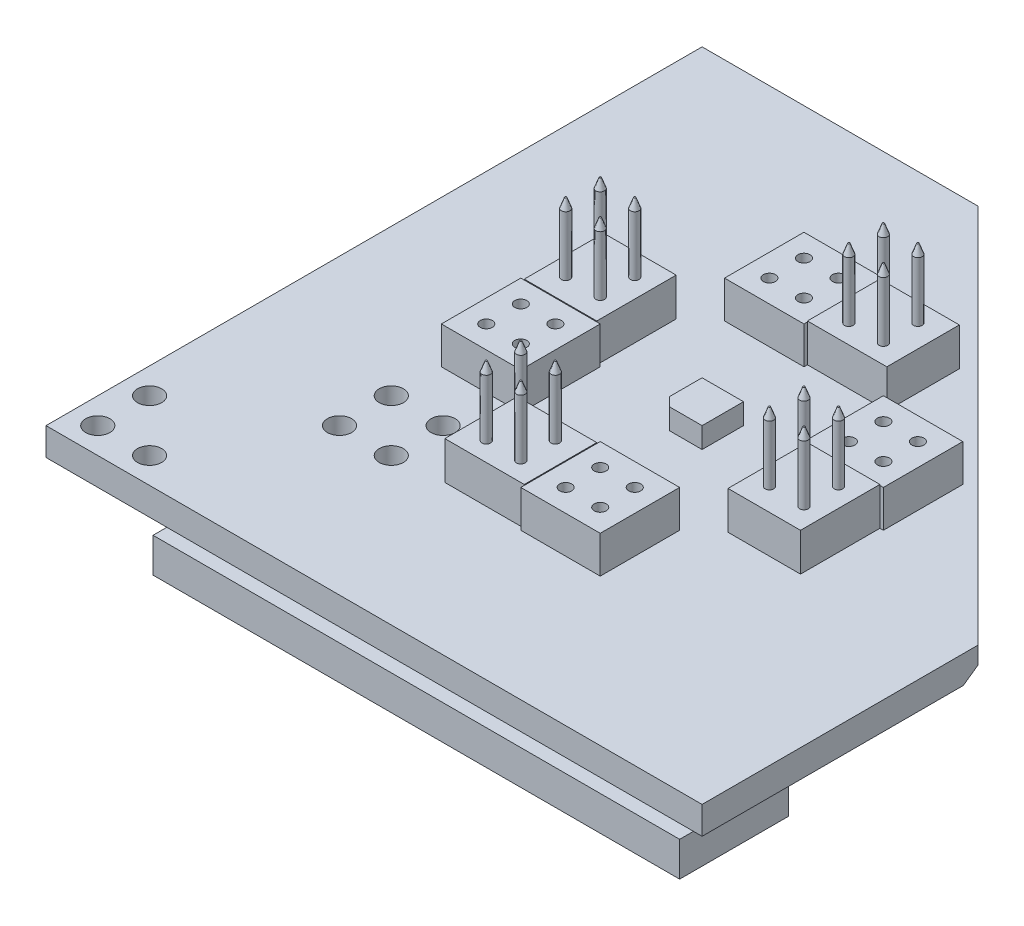
SolidWorks part; units mm, degrees
ref_plane "Front" through (0, 0, 0) normal (0, 0, 1) x (1, 0, 0)
ref_plane "Top" through (0, 0, 0) normal (0, 1, 0) x (1, 0, 0)
ref_plane "Right" through (0, 0, 0) normal (1, 0, 0) x (0, 0, -1)
sketch "Sketch1" plane through (0, 0, 0) normal (0, 1, 0) x (1, 0, 0)
  line L0 (19, -3.0194) -> (-3.0194, 19)
  line L1 (-19, 19) -> (-3.0194, 19)
  line L2 (-19, 19) -> (-19, -19)
  line L3 (-19, -19) -> (19, -19)
  line L4 (19, -3.0194) -> (19, -19)
  dimension "D1" = 19
  dimension "D2" = 19
  dimension "D3" = 19
  dimension "D4" = 19
  dimension "D5" = 45
  dimension "D6" = 11.3
extrude "Extrude1" add sketch "Sketch1" along normal blind 1.6
sketch "Sketch2" plane through (0, 1.6, 0) normal (0, 1, 0) x (-1, 0, 0)
  line L0 (-10.5, -4.6) -> (-10.5, 0)
  line L1 (4.6, -10.5) -> (0, -10.5)
  line L2 (4.6, -10.5) -> (4.6, -5.9)
  line L3 (4.6, -5.9) -> (0, -5.9)
  line L4 (0, -10.5) -> (0, -5.9)
  line L5 (-10.5, -4.6) -> (-5.9, -4.6)
  line L6 (-5.9, -4.6) -> (-5.9, 0)
  line L7 (-10.5, 0) -> (-5.9, 0)
  line L8 (-4.6, 10.5) -> (0, 10.5)
  line L9 (-4.6, 10.5) -> (-4.6, 5.9)
  line L10 (-4.6, 5.9) -> (0, 5.9)
  line L11 (0, 10.5) -> (0, 5.9)
  line L12 (10.5, 4.6) -> (10.5, 0)
  line L13 (10.5, 4.6) -> (5.9, 4.6)
  line L14 (5.9, 4.6) -> (5.9, 0)
  line L15 (10.5, 0) -> (5.9, 0)
  dimension "D1" = 4.6
  dimension "D2" = 4.6
  dimension "D3" = 5.9
  dimension "D4" = 5.9
extrude "Extrude2" add sketch "Sketch2" along normal blind 2.15
sketch "Sketch3" plane through (0, 1.6, 0) normal (0, 1, 0) x (-1, 0, 0)
  line L0 (0, -5.9) -> (0, -10.5) construction
  line L1 (-4.6, -10.3) -> (0, -10.3)
  line L2 (-4.6, -10.3) -> (-4.6, -6.1)
  line L3 (-4.6, -6.1) -> (0, -6.1)
  line L4 (0, -10.3) -> (0, -6.1)
  line L5 (-6.1, 4.6) -> (-6.1, 0)
  line L6 (-10.3, 0) -> (-6.1, 0)
  line L7 (-10.3, 4.6) -> (-6.1, 4.6)
  line L8 (-10.3, 4.6) -> (-10.3, 0)
  line L9 (4.6, 6.1) -> (0, 6.1)
  line L10 (0, 10.3) -> (0, 6.1)
  line L11 (4.6, 10.3) -> (4.6, 6.1)
  line L12 (4.6, 10.3) -> (0, 10.3)
  line L13 (6.1, -4.6) -> (6.1, 0)
  line L14 (10.3, 0) -> (6.1, 0)
  line L15 (10.3, -4.6) -> (6.1, -4.6)
  line L16 (10.3, -4.6) -> (10.3, 0)
  dimension "D1" = 4.6
  dimension "D2" = 4.2
  dimension "D3" = 6.1
  dimension "D4" = 6.1
extrude "Extrude3" add sketch "Sketch3" along normal blind 2.2
sketch "Sketch4" plane through (0, 3.75, 0) normal (0, 1, 0) x (-1, 0, 0)
  line L0 (2.3, -10.5) -> (2.3, -5.9) construction
  line L2 (4.6, -5.9) -> (0, -5.9) construction
  line L3 (4.6, -8.2) -> (0, -8.2) construction
  line L4 (0, -10.5) -> (4.6, -10.5) construction
  line L6 (4.6, -10.5) -> (4.6, -5.9) construction
  circle A0 centre (3.3, -9.2) radius 0.35
  circle A1 centre (1.3, -9.2) radius 0.35
  circle A2 centre (1.3, -7.2) radius 0.35
  circle A3 centre (3.3, -7.2) radius 0.35
  circle A4 centre (-9.2, -3.3) radius 0.35
  circle A5 centre (-9.2, -1.3) radius 0.35
  circle A6 centre (-7.2, -1.3) radius 0.35
  circle A7 centre (-7.2, -3.3) radius 0.35
  circle A8 centre (-3.3, 9.2) radius 0.35
  circle A9 centre (-1.3, 9.2) radius 0.35
  circle A10 centre (-1.3, 7.2) radius 0.35
  circle A11 centre (-3.3, 7.2) radius 0.35
  circle A12 centre (9.2, 3.3) radius 0.35
  circle A13 centre (9.2, 1.3) radius 0.35
  circle A14 centre (7.2, 1.3) radius 0.35
  circle A15 centre (7.2, 3.3) radius 0.35
  dimension "D3" = 0.7
  dimension "D1" = 1
  dimension "D2" = 1
extrude "Cut-Extrude1" cut sketch "Sketch4" against normal up to surface (2.15 mm away) up to face at (0, 1.6, 8.2)
sketch "Sketch5" plane through (0, 3.8, 0) normal (0, 1, 0) x (-1, 0, 0)
  line L0 (-2.3, -10.3) -> (-2.3, -6.1) construction
  line L1 (-4.6, -10.3) -> (0, -10.3) construction
  line L2 (0, -6.1) -> (-4.6, -6.1) construction
  line L3 (0, -8.2) -> (-4.6, -8.2) construction
  line L4 (0, -10.3) -> (0, -6.1) construction
  line L5 (-4.6, -6.1) -> (-4.6, -10.3) construction
  circle A0 centre (-1.3, -9.2) radius 0.25
  circle A1 centre (-3.3, -9.2) radius 0.25
  circle A2 centre (-3.3, -7.2) radius 0.25
  circle A3 centre (-1.3, -7.2) radius 0.25
  circle A4 centre (-7.2, 1.3) radius 0.25
  circle A5 centre (-9.2, 1.3) radius 0.25
  circle A6 centre (-9.2, 3.3) radius 0.25
  circle A7 centre (-7.2, 3.3) radius 0.25
  circle A8 centre (1.3, 7.2) radius 0.25
  circle A9 centre (1.3, 9.2) radius 0.25
  circle A10 centre (3.3, 9.2) radius 0.25
  circle A11 centre (3.3, 7.2) radius 0.25
  circle A12 centre (7.2, -1.3) radius 0.25
  circle A13 centre (9.2, -1.3) radius 0.25
  circle A14 centre (9.2, -3.3) radius 0.25
  circle A15 centre (7.2, -3.3) radius 0.25
  dimension "D3" = 0.5
  dimension "D1" = 1
  dimension "D2" = 1
extrude "Extrude4" add sketch "Sketch5" along normal blind 4
chamfer "Chamfer1" distance 0.2 angle 70 16 edges at (-1.3, 7.8, 9.45) (-3.3, 7.8, 8.95) (-3.3, 7.8, 7.45) (-1.3, 7.8, 6.95) (7.2, 7.8, 3.55) (9.2, 7.8, 3.05) (9.2, 7.8, 1.55) (7.2, 7.8, 1.05) (1.3, 7.8, -7.45) (3.3, 7.8, -6.95) (3.3, 7.8, -9.45) (1.3, 7.8, -8.95) (-9.2, 7.8, -1.05) (-7.2, 7.8, -3.05) (-9.2, 7.8, -3.55) (-7.2, 7.8, -1.55)
sketch "Sketch6" plane through (0, 0, 0) normal (0, -1, 0) x (1, 0, 0)
  line L0 (-19, -19) -> (-19, 19) construction
  line L1 (-13.5, -18.5) -> (-19.8, -18.5)
  line L2 (-19.8, -18.5) -> (-19.8, 12)
  line L3 (-19.8, 12) -> (-13.5, 12)
  line L4 (-13.5, 12) -> (-13.5, -18.5)
  line L8 (0, 0) -> (-19, 19) construction
  line L9 (18.5, 13.5) -> (18.5, 19.8)
  line L10 (18.5, 19.8) -> (-12, 19.8)
  line L11 (-12, 19.8) -> (-12, 13.5)
  line L12 (-12, 13.5) -> (18.5, 13.5)
  dimension "D1" = 30.5
  dimension "D2" = 6.3
  dimension "D3" = 13.5
  dimension "D4" = 18.5
extrude "Extrude5" add sketch "Sketch6" along normal blind 2
sketch "Sketch7" plane through (0, 0, 0) normal (0, -1, 0) x (1, 0, 0)
  line L0 (-19, 19) -> (-12, 19) construction
  line L1 (-8.75, 3.25) -> (-1.75, 3.25)
  line L2 (-8.75, 3.25) -> (-8.75, -3.75)
  line L3 (-8.75, -3.75) -> (-1.75, -3.75)
  line L4 (-1.75, 3.25) -> (-1.75, -3.75)
  line L5 (-19, 12) -> (-19, 19) construction
  dimension "D1" = 7
  dimension "D2" = 7
  dimension "D3" = 15.75
  dimension "D4" = 10.25
extrude "Extrude6" add sketch "Sketch7" along normal blind 1
chamfer "Chamfer2" distance 0.6 angle 45 1 edges at (7.9903, 0, -7.9903)
sketch "Sketch8" plane through (0, 1.6, 0) normal (0, 1, 0) x (-1, 0, 0)
  line L0 (1.2, 0.7) -> (0.7, 1.2)
  line L1 (1.2, -1.2) -> (-1.2, -1.2)
  line L2 (1.2, -1.2) -> (1.2, 0.7)
  line L3 (0.7, 1.2) -> (-1.2, 1.2)
  line L4 (-1.2, -1.2) -> (-1.2, 1.2)
  dimension "D1" = 1.2
  dimension "D2" = 1.2
  dimension "D3" = 1.2
  dimension "D4" = 1.2
  dimension "D5" = 0.5
  dimension "D6" = 0.5
extrude "Extrude7" add sketch "Sketch8" along normal blind 1.2
sketch "Sketch9" plane through (0, 0, 0) normal (0, -1, 0) x (1, 0, 0)
  line L0 (19, 19) -> (19, 3.8679) construction
  line L1 (9.5, 1.7) -> (7.5, 1.7)
  line L2 (9.5, 1.7) -> (9.5, -0.3)
  line L3 (9.5, -0.3) -> (7.5, -0.3)
  line L4 (7.5, 1.7) -> (7.5, -0.3)
  line L5 (18.5, 19) -> (19, 19) construction
  line L6 (-19, 19) -> (-12, 19) construction
  line L7 (-0.35, 6.15) -> (-2.35, 6.15)
  line L8 (-0.35, 6.15) -> (-0.35, 4.15)
  line L9 (-0.35, 4.15) -> (-2.35, 4.15)
  line L10 (-2.35, 6.15) -> (-2.35, 4.15)
  dimension "D1" = 9.5
  dimension "D2" = 17.3
  dimension "D3" = 2
  dimension "D4" = 2
  dimension "D5" = 19.35
  dimension "D6" = 12.85
  dimension "D7" = 2
  dimension "D8" = 2
extrude "Extrude8" add sketch "Sketch9" along normal blind 0.9
sketch "Sketch10" plane through (0, 0, 0) normal (0, -1, 0) x (1, 0, 0)
  line L0 (19, 19) -> (19, 3.8679) construction
  line L1 (1.35, 2.8) -> (0.6, 2.8)
  line L2 (1.55, 2.6) -> (1.55, -0.2)
  line L3 (1.35, -0.4) -> (0.6, -0.4)
  line L4 (0.4, 2.6) -> (0.4, -0.2)
  line L5 (-19, 19) -> (-12, 19) construction
  arc A0 (0.4, -0.2) -> (0.6, -0.4) centre (0.6, -0.2) ccw
  arc A1 (0.6, 2.8) -> (0.4, 2.6) centre (0.6, 2.6) ccw
  arc A2 (1.55, 2.6) -> (1.35, 2.8) centre (1.35, 2.6) ccw
  arc A3 (1.35, -0.4) -> (1.55, -0.2) centre (1.35, -0.2) ccw
  point P10 (0.4, -0.4)
  point P15 (1.55, 2.8)
  point P18 (1.55, -0.4)
  dimension "D5" = 0.2
  dimension "D1" = 17.45
  dimension "D2" = 16.2
  dimension "D3" = 1.15
  dimension "D4" = 3.2
extrude "Extrude9" add sketch "Sketch10" along normal blind 1
sketch "Sketch11" plane through (0, 0, 0) normal (0, -1, 0) x (1, 0, 0)
  line L0 (19, 19) -> (19, 3.8679) construction
  line L1 (9.35, 6.9) -> (7.75, 6.9)
  line L2 (9.35, 6.9) -> (9.35, 6.1)
  line L3 (9.35, 6.1) -> (7.75, 6.1)
  line L4 (7.75, 6.9) -> (7.75, 6.1)
  line L5 (-19, 19) -> (-12, 19) construction
  line L6 (-19, 12) -> (-19, 19) construction
  line L7 (-10.15, -6.9) -> (-10.95, -6.9)
  line L8 (-10.15, -6.9) -> (-10.15, -5.3)
  line L9 (-10.15, -5.3) -> (-10.95, -5.3)
  line L10 (-10.95, -6.9) -> (-10.95, -5.3)
  line L11 (-3.8679, -19) -> (-19, -19) construction
  line L12 (-19, -19) -> (-19, -18.5) construction
  line L13 (-2.9, -14.85) -> (-3.7, -14.85)
  line L14 (-2.9, -14.85) -> (-2.9, -13.25)
  line L15 (-2.9, -13.25) -> (-3.7, -13.25)
  line L16 (-3.7, -14.85) -> (-3.7, -13.25)
  line L18 (-0.3, -12.1) -> (-1.1, -12.1)
  line L19 (-0.3, -12.1) -> (-0.3, -10.5)
  line L20 (-0.3, -10.5) -> (-1.1, -10.5)
  line L21 (-1.1, -12.1) -> (-1.1, -10.5)
  point P20 (-19, -18.75)
  point P27 (-19, -18.75)
  dimension "D1" = 9.65
  dimension "D2" = 12.1
  dimension "D3" = 1.6
  dimension "D4" = 0.8
  dimension "D5" = 8.05
  dimension "D6" = 12.1
  dimension "D7" = 1.6
  dimension "D8" = 0.8
  dimension "D9" = 15.3
  dimension "D10" = 4.15
  dimension "D11" = 1.6
  dimension "D12" = 0.8
  dimension "D13" = 17.9
  dimension "D14" = 6.9
  dimension "D15" = 1.6
  dimension "D16" = 0.8
extrude "Extrude10" add sketch "Sketch11" along normal blind 0.5
sketch "Sketch12" plane through (0, 0, 0) normal (0, -1, 0) x (1, 0, 0)
  line L0 (-19, 12) -> (-19, 19) construction
  line L1 (-11.3, -16.3) -> (-9.6, -16.3)
  line L2 (-11.3, -16.3) -> (-11.3, -12.6)
  line L3 (-11.3, -12.6) -> (-10.6, -12.6)
  line L4 (-4.6, -16.3) -> (-4.6, -12.6)
  line L5 (-3.8679, -19) -> (-19, -19) construction
  line L6 (-6.4, -16.3) -> (-4.6, -16.3)
  line L7 (-9.7, -12.6) -> (-8.45, -12.6)
  line L8 (-6.4, -16.3) -> (-6.4, -18.2)
  line L9 (-6.4, -18.2) -> (-9.6, -18.2)
  line L10 (-9.6, -16.3) -> (-9.6, -18.2)
  line L11 (-5.3, -12.6) -> (-4.6, -12.6)
  line L12 (-5.3, -12.6) -> (-5.3, -10.7)
  line L13 (-5.3, -10.7) -> (-6.2, -10.7)
  line L14 (-6.2, -12.6) -> (-6.2, -10.7)
  line L16 (-7.55, -12.6) -> (-7.55, -10.7)
  line L17 (-7.55, -10.7) -> (-8.45, -10.7)
  line L18 (-8.45, -12.6) -> (-8.45, -10.7)
  line L19 (-7.55, -12.6) -> (-6.2, -12.6)
  line L20 (-9.7, -12.6) -> (-9.7, -10.7)
  line L21 (-9.7, -10.7) -> (-10.6, -10.7)
  line L22 (-10.6, -12.6) -> (-10.6, -10.7)
  dimension "D1" = 7.7
  dimension "D2" = 2.7
  dimension "D3" = 6.7
  dimension "D4" = 3.7
  dimension "D5" = 1.9
  dimension "D6" = 3.2
  dimension "D7" = 1.7
  dimension "D8" = 0.9
  dimension "D9" = 1.9
  dimension "D10" = 0.9
  dimension "D11" = 1.9
  dimension "D12" = 0.9
  dimension "D13" = 1.9
  dimension "D14" = 2.85
  dimension "D15" = 0.7
  dimension "D16" = 0.7
extrude "Extrude11" add sketch "Sketch12" along normal blind 0.3
sketch "Sketch13" plane through (0, -0.3, 0) normal (0, -1, 0) x (1, 0, 0)
  line L1 (-4.61, -16.29) -> (-11.29, -16.29)
  line L2 (-4.61, -16.29) -> (-4.61, -12.61)
  line L3 (-4.61, -12.61) -> (-11.29, -12.61)
  line L4 (-11.29, -16.29) -> (-11.29, -12.61)
  line L5 (-6.4, -16.3) -> (-4.6, -16.3) construction
  line L6 (-4.6, -16.3) -> (-4.6, -12.6) construction
  line L7 (-11.3, -12.6) -> (-11.3, -16.3) construction
  line L8 (-10.6, -12.6) -> (-11.3, -12.6) construction
  dimension "D1" = 0.01
  dimension "D2" = 0.01
  dimension "D3" = 0.01
  dimension "D4" = 0.01
extrude "Extrude12" add sketch "Sketch13" along normal blind 1.5
sketch "Sketch14" plane through (0, 0, 0) normal (0, -1, 0) x (1, 0, 0)
  line L0 (-19, 12) -> (-19, 19) construction
  line L1 (-19, 19) -> (-12, 19) construction
  line L2 (0, 0) -> (-19, 19) construction
  circle A0 centre (-17.5, 17.5) radius 0.7
  circle A1 centre (-17.5, 14.5) radius 0.7
  circle A2 centre (-10.5, 10.5) radius 0.7
  circle A3 centre (-7.5, 7.5) radius 0.7
  circle A4 centre (-10.5, 7.5) radius 0.7
  circle A5 centre (-14.5, 17.5) radius 0.7
  circle A6 centre (-7.5, 10.5) radius 0.7
  dimension "D1" = 1.4
  dimension "D5" = 1.4
  dimension "D7" = 1.4
  dimension "D8" = 1.4
  dimension "D11" = 1.4
  dimension "D2" = 1.5
  dimension "D3" = 1.5
  dimension "D4" = 3
  dimension "D6" = 1.5
  dimension "D9" = 8.5
  dimension "D10" = 3
  dimension "D12" = 3
  dimension "D13" = 3
extrude "Cut-Extrude2" cut sketch "Sketch14" against normal through all
sketch "Sketch15" plane through (0, 0, 0) normal (0, -1, 0) x (1, 0, 0)
  line L0 (-19, 12) -> (-19, 19) construction
  line L1 (-8.6, 7.0444) -> (-7.9556, 6.4)
  line L2 (-7.9556, 6.4) -> (-7.0444, 6.4)
  line L3 (-7.0444, 6.4) -> (-6.4, 7.0444)
  line L4 (-6.4, 7.0444) -> (-6.4, 7.9556)
  line L5 (-6.4, 7.9556) -> (-7.0444, 8.6)
  line L6 (-7.0444, 8.6) -> (-7.9556, 8.6)
  line L7 (-7.9556, 8.6) -> (-8.6, 7.9556)
  line L8 (-8.6, 7.9556) -> (-8.6, 7.0444)
  line L9 (-11.6, 7.0444) -> (-10.9556, 6.4)
  line L10 (-10.9556, 6.4) -> (-10.0444, 6.4)
  line L11 (-10.0444, 6.4) -> (-9.4, 7.0444)
  line L12 (-9.4, 7.0444) -> (-9.4, 7.9556)
  line L13 (-9.4, 7.9556) -> (-10.0444, 8.6)
  line L14 (-10.0444, 8.6) -> (-10.9556, 8.6)
  line L15 (-10.9556, 8.6) -> (-11.6, 7.9556)
  line L16 (-11.6, 7.9556) -> (-11.6, 7.0444)
  line L17 (-8.6, 10.0444) -> (-7.9556, 9.4)
  line L18 (-7.9556, 9.4) -> (-7.0444, 9.4)
  line L19 (-7.0444, 9.4) -> (-6.4, 10.0444)
  line L20 (-6.4, 10.0444) -> (-6.4, 10.9556)
  line L21 (-6.4, 10.9556) -> (-7.0444, 11.6)
  line L22 (-7.0444, 11.6) -> (-7.9556, 11.6)
  line L23 (-7.9556, 11.6) -> (-8.6, 10.9556)
  line L24 (-8.6, 10.9556) -> (-8.6, 10.0444)
  line L25 (-11.6, 10.0444) -> (-10.9556, 9.4)
  line L26 (-10.9556, 9.4) -> (-10.0444, 9.4)
  line L27 (-10.0444, 9.4) -> (-9.4, 10.0444)
  line L28 (-9.4, 10.0444) -> (-9.4, 10.9556)
  line L29 (-9.4, 10.9556) -> (-10.0444, 11.6)
  line L30 (-10.0444, 11.6) -> (-10.9556, 11.6)
  line L31 (-10.9556, 11.6) -> (-11.6, 10.9556)
  line L32 (-11.6, 10.9556) -> (-11.6, 10.0444)
  line L33 (-18.6, 14.0444) -> (-17.9556, 13.4)
  line L34 (-17.9556, 13.4) -> (-17.0444, 13.4)
  line L35 (-17.0444, 13.4) -> (-16.4, 14.0444)
  line L36 (-16.4, 14.0444) -> (-16.4, 14.9556)
  line L37 (-16.4, 14.9556) -> (-17.0444, 15.6)
  line L38 (-17.0444, 15.6) -> (-17.9556, 15.6)
  line L39 (-17.9556, 15.6) -> (-18.6, 14.9556)
  line L40 (-18.6, 14.9556) -> (-18.6, 14.0444)
  line L41 (-18.6, 17.0444) -> (-17.9556, 16.4)
  line L42 (-17.9556, 16.4) -> (-17.0444, 16.4)
  line L43 (-17.0444, 16.4) -> (-16.4, 17.0444)
  line L44 (-16.4, 17.0444) -> (-16.4, 17.9556)
  line L45 (-16.4, 17.9556) -> (-17.0444, 18.6)
  line L46 (-17.0444, 18.6) -> (-17.9556, 18.6)
  line L47 (-17.9556, 18.6) -> (-18.6, 17.9556)
  line L48 (-18.6, 17.9556) -> (-18.6, 17.0444)
  line L49 (-15.6, 17.0444) -> (-14.9556, 16.4)
  line L50 (-14.9556, 16.4) -> (-14.0444, 16.4)
  line L51 (-14.0444, 16.4) -> (-13.4, 17.0444)
  line L52 (-13.4, 17.0444) -> (-13.4, 17.9556)
  line L53 (-13.4, 17.9556) -> (-14.0444, 18.6)
  line L54 (-14.0444, 18.6) -> (-14.9556, 18.6)
  line L55 (-14.9556, 18.6) -> (-15.6, 17.9556)
  line L56 (-15.6, 17.9556) -> (-15.6, 17.0444)
  circle A0 centre (-7.5, 7.5) radius 1.1 construction
  circle A1 centre (-10.5, 7.5) radius 1.1 construction
  circle A2 centre (-7.5, 10.5) radius 1.1 construction
  circle A3 centre (-10.5, 10.5) radius 1.1 construction
  circle A4 centre (-17.5, 14.5) radius 1.1 construction
  circle A5 centre (-17.5, 17.5) radius 1.1 construction
  circle A6 centre (-14.5, 17.5) radius 1.1 construction
  circle A7 centre (-7.5, 7.5) radius 0.7 construction
  circle A8 centre (-7.5, 7.5) radius 0.7
  circle A9 centre (-10.5, 7.5) radius 0.7 construction
  circle A10 centre (-10.5, 7.5) radius 0.7
  circle A11 centre (-7.5, 10.5) radius 0.7 construction
  circle A12 centre (-7.5, 10.5) radius 0.7
  circle A13 centre (-10.5, 10.5) radius 0.7 construction
  circle A14 centre (-10.5, 10.5) radius 0.7
  circle A15 centre (-14.5, 17.5) radius 0.7 construction
  circle A16 centre (-14.5, 17.5) radius 0.7
  circle A17 centre (-17.5, 14.5) radius 0.7 construction
  circle A18 centre (-17.5, 14.5) radius 0.7
  circle A19 centre (-17.5, 17.5) radius 0.7 construction
  circle A20 centre (-17.5, 17.5) radius 0.7
  dimension "D1" = 2.2
  dimension "D2" = 2.2
  dimension "D3" = 2.2
  dimension "D4" = 2.2
  dimension "D5" = 2.2
  dimension "D6" = 2.2
  dimension "D7" = 2.2
extrude "Extrude13" add sketch "Sketch15" along normal blind 0.05 and the other way blind 1.05
sketch "Sketch16" plane through (0, 0, 0) normal (0, -1, 0) x (1, 0, 0)
  line L0 (-19, -19) -> (-19, -18.5) construction
  line L1 (-7.2, -8.2) -> (-10.6, -8.2)
  line L2 (-7.2, -8.2) -> (-7.2, -9.9)
  line L3 (-7.2, -9.9) -> (-10.6, -9.9)
  line L4 (-10.6, -8.2) -> (-10.6, -9.9)
  line L5 (-3.8679, -19) -> (-19, -19) construction
  dimension "D1" = 8.4
  dimension "D2" = 9.1
  dimension "D3" = 1.7
  dimension "D4" = 3.4
extrude "Extrude14" add sketch "Sketch16" along normal blind 1.6
sketch "Sketch17" plane through (0, 0, 0) normal (0, -1, 0) x (1, 0, 0)
  line L0 (-19, -19) -> (-19, -18.5) construction
  line L1 (-8.05, -5) -> (-9.25, -5)
  line L2 (-8.05, -5) -> (-8.05, -7.3)
  line L3 (-8.05, -7.3) -> (-9.25, -7.3)
  line L4 (-9.25, -5) -> (-9.25, -7.3)
  line L5 (-3.8679, -19) -> (-19, -19) construction
  point P4 (-19, -18.75)
  dimension "D1" = 9.75
  dimension "D2" = 11.7
  dimension "D3" = 1.2
  dimension "D4" = 2.3
extrude "Extrude15" add sketch "Sketch17" along normal blind 1.3
sketch "Sketch18" plane through (0, 0, 0) normal (0, -1, 0) x (1, 0, 0)
  line L0 (-19, -19) -> (-19, -18.5) construction
  line L1 (-3.65, -12.05) -> (-1.65, -12.05)
  line L2 (-3.65, -12.05) -> (-3.65, -11.05)
  line L3 (-3.65, -11.05) -> (-1.65, -11.05)
  line L4 (-1.65, -12.05) -> (-1.65, -11.05)
  line L5 (-3.8679, -19) -> (-19, -19) construction
  point P4 (-19, -18.75)
  dimension "D1" = 15.35
  dimension "D2" = 6.95
  dimension "D3" = 2
  dimension "D4" = 1
extrude "Extrude16" add sketch "Sketch18" along normal blind 0.5
sketch "Sketch19" plane through (0, 0, 0) normal (0, -1, 0) x (1, 0, 0)
  line L0 (-19, -19) -> (-19, -18.5) construction
  line L1 (-0.8, -8.45) -> (0.45, -8.45)
  line L2 (-0.8, -8.45) -> (-0.8, -7)
  line L3 (-0.8, -7) -> (-0.5, -7)
  line L4 (2.25, -8.45) -> (2.25, -7)
  line L5 (-3.8679, -19) -> (-19, -19) construction
  line L6 (1.95, -7) -> (2.25, -7)
  line L8 (0.95, -8.45) -> (0.95, -9.05)
  line L9 (0.95, -9.05) -> (0.45, -9.05)
  line L10 (0.45, -8.45) -> (0.45, -9.05)
  line L11 (0, -7) -> (1.45, -7)
  line L12 (1.95, -7) -> (1.95, -6.4)
  line L13 (1.95, -6.4) -> (1.45, -6.4)
  line L14 (1.45, -7) -> (1.45, -6.4)
  line L15 (0.95, -8.45) -> (2.25, -8.45)
  line L16 (0, -7) -> (0, -6.4)
  line L17 (0, -6.4) -> (-0.5, -6.4)
  line L18 (-0.5, -7) -> (-0.5, -6.4)
  dimension "D1" = 18.2
  dimension "D2" = 10.55
  dimension "D3" = 1.45
  dimension "D4" = 3.05
  dimension "D5" = 0.5
  dimension "D6" = 0.6
  dimension "D7" = 0.5
  dimension "D8" = 0.5
  dimension "D9" = 0.6
  dimension "D10" = 0.6
  dimension "D11" = 1.25
  dimension "D12" = 0.3
  dimension "D13" = 0.3
extrude "Extrude17" add sketch "Sketch19" along normal blind 0.3
sketch "Sketch20" plane through (0, -0.3, 0) normal (0, -1, 0) x (1, 0, 0)
  line L0 (-0.8, -7) -> (-0.8, -8.45) construction
  line L1 (-0.79, -7.01) -> (2.24, -7.01)
  line L2 (-0.79, -7.01) -> (-0.79, -8.44)
  line L3 (-0.79, -8.44) -> (2.24, -8.44)
  line L4 (2.24, -7.01) -> (2.24, -8.44)
  line L5 (-0.5, -7) -> (-0.8, -7) construction
  line L6 (-0.8, -8.45) -> (0.45, -8.45) construction
  line L7 (2.25, -8.45) -> (2.25, -7) construction
  dimension "D1" = 0.01
  dimension "D2" = 0.01
  dimension "D3" = 0.01
  dimension "D4" = 0.01
extrude "Extrude18" add sketch "Sketch20" along normal blind 0.8
